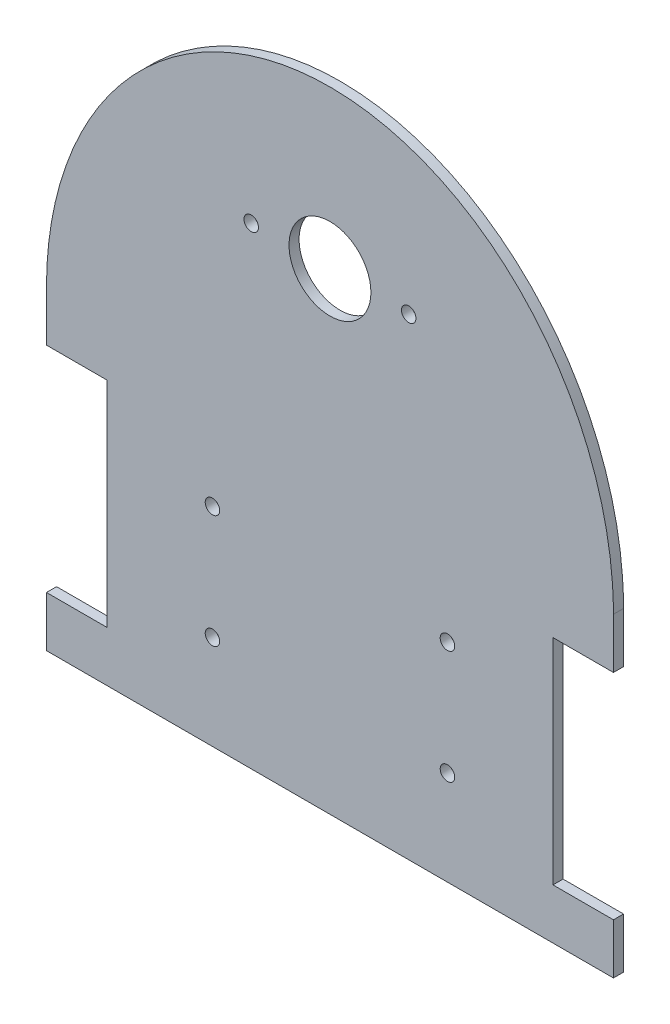
SolidWorks part; units mm, degrees
material "A-Glass Fiber"
ref_plane "Top Plane" through (0, 0, 0) normal (0, 0, 1) x (1, 0, 0)
ref_plane "Right Plane" through (0, 0, 0) normal (0, 1, 0) x (1, 0, 0)
ref_plane "Front Plane" through (0, 0, 0) normal (1, 0, 0) x (0, 0, -1)
sketch "Sketch1" plane through (0, 0, 0) normal (0, 0, 1) x (1, 0, 0)
  line L1 (45, -50) -> (-45, -50)
  line L2 (45, -50) -> (45, 50)
  line L3 (45, 50) -> (-45, 50)
  line L4 (-45, -50) -> (-45, 50)
  line L5 (45, -50) -> (-45, 50) construction
  line L6 (45, 50) -> (-45, -50) construction
  point P0 (0, 0)
  dimension "D1" = 90
  dimension "D2" = 100
extrude "Boss-Extrude1" add sketch "Sketch1" along normal blind 1.6
sketch "Sketch2" plane through (0, 0, 1.6) normal (0, 0, 1) x (1, 0, 0)
  line L0 (-45, 50) -> (-45, -50) construction
  line L1 (45, 50) -> (-45, 50) construction
  line L6 (-45, 0) -> (-70, 0)
  line L7 (-70, 0) -> (-70, 70)
  line L8 (45, -50) -> (45, 50) construction
  line L9 (-70, 70) -> (70, 70)
  line L10 (70, 70) -> (70, 0)
  line L11 (70, 0) -> (45, 0)
  ellipse E0 centre (0, 0) end of major axis (0, -50) minor radius 45 (45, 0) -> (-45, 0) ccw
  point P14 (0, 70)
  dimension "D1" = 140
  dimension "D2" = 70
extrude "Cut-Extrude1" cut sketch "Sketch2" against normal through all
sketch "Sketch3" plane through (0, 0, 1.6) normal (0, 0, 1) x (1, 0, 0)
  line L1 (-45, -8) -> (-35.4, -8)
  line L2 (-45, -8) -> (-45, -42)
  line L3 (-45, -42) -> (-35.4, -42)
  line L4 (-35.4, -8) -> (-35.4, -42)
  line L6 (0, -55) -> (0, 55) construction
  line L7 (45, -8) -> (35.4, -8)
  line L8 (45, -42) -> (35.4, -42)
  line L9 (35.4, -8) -> (35.4, -42)
  line L10 (45, -8) -> (45, -42)
  line L11 (-45, 0) -> (-45, -50) construction
  line L13 (-45, -50) -> (45, -50) construction
  dimension "D1" = 9.6
  dimension "D2" = 34
  dimension "D3" = 8
extrude "Cut-Extrude2" cut sketch "Sketch3" against normal through all
sketch "Sketch4" plane through (0, 0, 1.6) normal (0, 0, 1) x (1, 0, 0)
  line L0 (-45, -50) -> (45, -50) construction
  circle A0 centre (0, 25) radius 6.5
  dimension "D1" = 13
  dimension "D2" = 75
extrude "Cut-Extrude3" cut sketch "Sketch4" against normal through all
sketch "Sketch5" plane through (0, 0, 1.6) normal (0, 0, 1) x (1, 0, 0)
  line L0 (-45, -42) -> (-35.4, -42) construction
  line L1 (-35.4, -42) -> (-35.4, -8) construction
  line L3 (0, -0.88) -> (0, 0.88) construction
  circle A0 centre (-18.65, -17) radius 1.15
  circle A1 centre (-18.65, -35) radius 1.15
  circle A2 centre (18.65, -35) radius 1.15
  circle A3 centre (18.65, -17) radius 1.15
  point P7 (-17.9638, -12)
  point P14 (0, 0)
  dimension "D3" = 2.3
  dimension "D1" = 7
  dimension "D2" = 18
  dimension "D4" = 16.75
extrude "Cut-Extrude4" cut sketch "Sketch5" against normal through all
sketch "Sketch6" plane through (0, 0, 1.6) normal (0, 0, 1) x (1, 0, 0)
  line L0 (-12.5, 25) -> (12.5, 25) construction
  circle A1 centre (-12.5, 25) radius 1.15
  circle A2 centre (12.5, 25) radius 1.15
  point P2 (-12.7045, 20)
  point P5 (0, 25)
  dimension "D2" = 2.3
  dimension "D1" = 25
extrude "Cut-Extrude5" cut sketch "Sketch6" against normal through all
equation "\"pozicija motora\" = 8"
equation "\"D3@Sketch3\"=\"pozicija motora\""
equation "\"pozicija castera\" = 75"
equation "\"D2@Sketch4\"=\"pozicija castera\""
